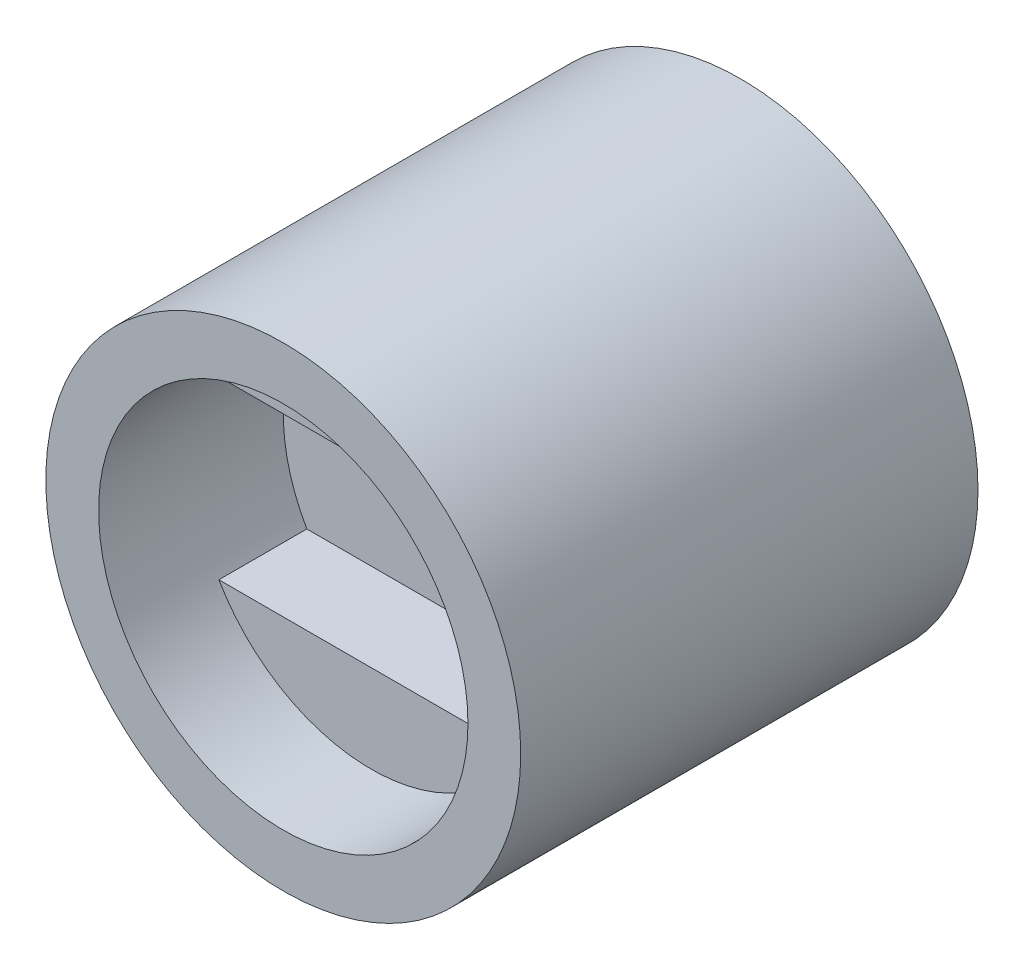
SolidWorks part; units mm, degrees
ref_plane "Plano frontal" through (0, 0, 0) normal (0, 0, 1) x (1, 0, 0)
ref_plane "Plano superior" through (0, 0, 0) normal (0, 1, 0) x (1, 0, 0)
ref_plane "Plano direito" through (0, 0, 0) normal (1, 0, 0) x (0, 0, -1)
sketch "Esboço1" plane through (0, 0, 0) normal (0, 0, 1) x (1, 0, 0)
  circle A0 centre (0, 0) radius 10
  dimension "D1" = 20
extrude "Ressalto-extrusão1" add sketch "Esboço1" along normal blind 16
sketch "Esboço5" plane through (0, 0, 16) normal (0, 0, 1) x (1, 0, 0)
  circle A0 centre (0, 0) radius 2.5
  dimension "D1" = 5
extrude "Corte-extrusão3" cut sketch "Esboço5" against normal up to next
sketch "Esboço2" plane through (0, 0, 16) normal (0, 0, 1) x (1, 0, 0)
  line L1 (-8.6603, 5) -> (8.6603, 5)
  line L3 (-8.6603, -5) -> (8.6603, -5)
  arc A0 (8.6603, -5) -> (8.6603, 5) centre (0, 0) ccw
  circle A1 centre (0, 0) radius 10
  arc A2 (-8.6603, 5) -> (-8.6603, -5) centre (0, 0) ccw
  dimension "D2" = 5
  dimension "D3" = 5
  dimension "D1" = 0
extrude "Corte-extrusão1" cut sketch "Esboço2" against normal blind 5
sketch "Esboço4" plane through (0, 0, 0) normal (0, 0, -1) x (-1, 0, 0)
  line L2 (-5, 8.6603) -> (-5, -8.6603)
  line L4 (5, 8.6603) -> (5, -8.6603)
  circle A0 centre (0, 0) radius 10 construction
  arc A1 (-5, -8.6603) -> (5, -8.6603) centre (0, 0) ccw
  arc A2 (5, 8.6603) -> (-5, 8.6603) centre (0, 0) ccw
  dimension "D1" = 5
  dimension "D2" = 5
extrude "Corte-extrusão2" cut sketch "Esboço4" against normal blind 5
sketch "Croquis1" plane through (0, 0, 16) normal (0, 0, 1) x (1, 0, 0)
  circle A0 centre (0, 0) radius 10.5
  circle A1 centre (0, 0) radius 13.5
  dimension "D1" = 27
  dimension "D2" = 21
extrude "Saliente-Extruir1" add sketch "Croquis1" along normal blind 5 and the other way blind 21
